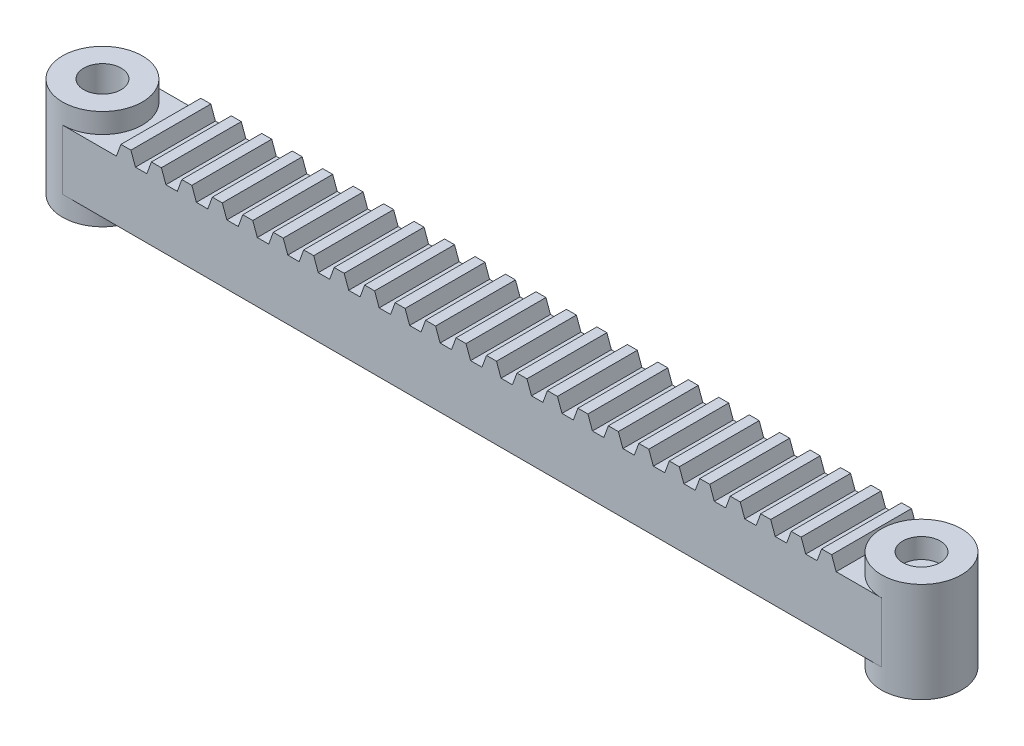
SolidWorks part; units mm, degrees
ref_plane "Front Plane" through (0, 0, 0) normal (0, 0, 1) x (1, 0, 0)
ref_plane "Top Plane" through (0, 0, 0) normal (0, 1, 0) x (1, 0, 0)
ref_plane "Right Plane" through (0, 0, 0) normal (1, 0, 0) x (0, 0, -1)
sketch "Sketch2" plane through (0, 0, 0) normal (0, 1, 0) x (1, 0, 0)
  circle A0 centre (-82, 0) radius 8
  circle A1 centre (82, 0) radius 8
  circle A2 centre (-82, 0) radius 3.75
  circle A3 centre (82, 0) radius 3.75
  point P6 (0, 0)
  dimension "D1" = 16
  dimension "D2" = 7.5
  dimension "D3" = 16
  dimension "D4" = 7.5
  dimension "D5" = 164
extrude "Boss-Extrude1" add sketch "Sketch2" along normal blind 20
ref_plane "Plane1" through (0, 16, 0) normal (0, 1, 0) x (1, 0, 0)
sketch "Sketch4" plane through (0, 16, 0) normal (0, 1, 0) x (1, 0, 0)
  line L1 (82, 8) -> (-82, 8)
  line L2 (82, 8) -> (82, -8)
  line L3 (82, -8) -> (-82, -8)
  line L4 (-82, 8) -> (-82, -8)
  line L5 (82, 8) -> (-82, -8) construction
  line L6 (82, -8) -> (-82, 8) construction
  circle A0 centre (-82, 0) radius 8 construction
  point P0 (0, 0)
extrude "Boss-Extrude2" add sketch "Sketch4" against normal blind 12
sketch "Sketch5" plane through (0, 0, 8) normal (0, 0, 1) x (1, 0, 0)
  line L1 (-82, 16) -> (82, 16) construction
  line L2 (72.9099, 16) -> (72, 18.5)
  line L3 (72, 18.5) -> (70, 18.5)
  line L4 (70, 18.5) -> (69.0901, 16)
  line L9 (69.0901, 16) -> (72.9099, 16)
  point P0 (71, 18.5)
  point P14 (71, 16)
  dimension "D1" = 2.5
  dimension "D2" = 18
  dimension "D3" = 2
  dimension "D5" = 40
extrude "Boss-Extrude3" add sketch "Sketch5" against normal through all
pattern_linear "LPattern2" count 24 spacing 6.1 along (-1, 0, 0) of "Boss-Extrude3"
